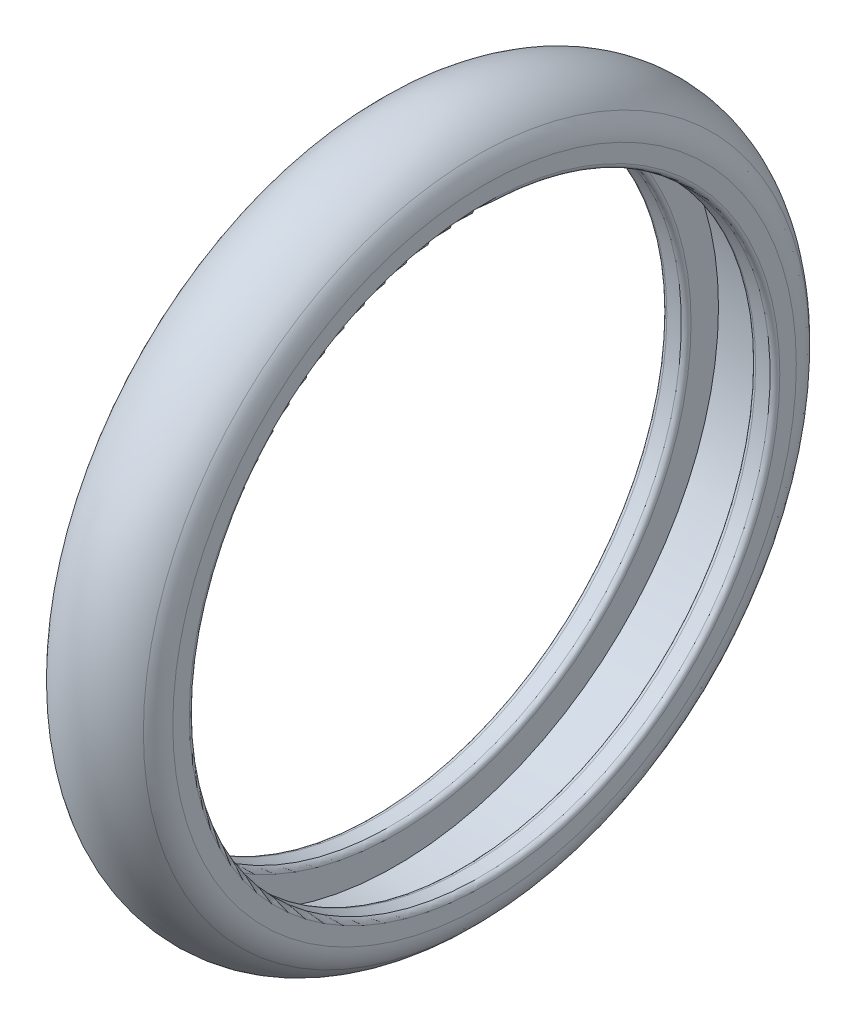
SolidWorks part; units mm, degrees
ref_plane "Ebene vorne" through (0, 0, 0) normal (0, 0, 1) x (1, 0, 0)
ref_plane "Ebene oben" through (0, 0, 0) normal (0, 1, 0) x (1, 0, 0)
ref_plane "Ebene rechts" through (0, 0, 0) normal (1, 0, 0) x (0, 0, -1)
sketch "Skizze2" plane through (0, 0, 0) normal (0, 0, 1) x (1, 0, 0)
  line L0 (0, 0) -> (0, 20) construction
  line L1 (2, 20) -> (-2, 20)
  line L2 (-2, 20) -> (-2, 18)
  line L3 (-2, 18) -> (-3.5, 18)
  line L4 (-3.5, 18) -> (-3.5, 19.9365)
  line L5 (3.5, 18) -> (3.5, 19.9365)
  line L6 (2, 18) -> (3.5, 18)
  line L7 (2, 20) -> (2, 18)
  line L8 (0, 0) -> (5.4917, 0) construction
  arc A0 (-3.5, 19.9365) -> (3.5, 19.9365) centre (0, 18) cw
  dimension "D2" = 4
  dimension "D6" = 18
  dimension "D1" = 36
  dimension "D3" = 7
  dimension "D4" = 4
  dimension "D5" = 2
revolve "Rotation1" add sketch "Skizze2" angle 360 about L8
fillet "Verrundung1" radius 2 2 edges at (-3.5, 0, 19.9365) (3.5, 0, 19.9365)
fillet "Verrundung2" radius 0.3 4 edges at (2, 0, 18) (-2, 0, 18) (-3.5, 0, 18) (3.5, 0, 18)
